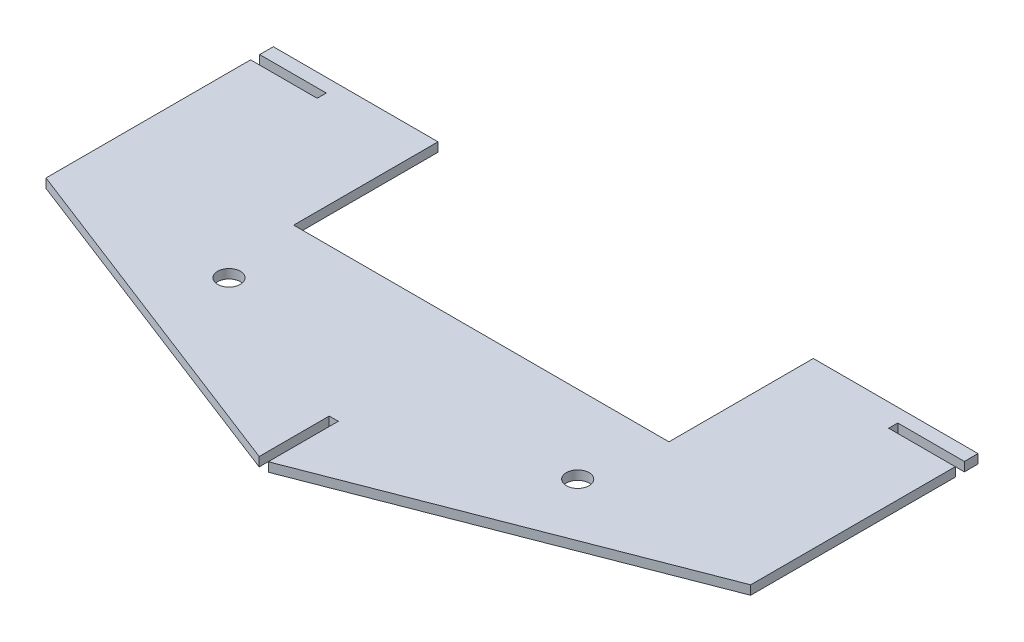
SolidWorks part; units mm, degrees
ref_plane "Front Plane" through (0, 0, 0) normal (0, 0, 1) x (1, 0, 0)
ref_plane "Top Plane" through (0, 0, 0) normal (0, 1, 0) x (1, 0, 0)
ref_plane "Right Plane" through (0, 0, 0) normal (1, 0, 0) x (0, 0, -1)
sketch "Sketch1" plane through (0, 0, 0) normal (0, 1, 0) x (1, 0, 0)
  line L0 (0, -100) -> (155, -160)
  line L1 (0, 0) -> (310, 0)
  line L2 (0, 0) -> (0, -100)
  line L3 (0, -100) -> (310, -100)
  line L4 (310, 0) -> (310, -100)
  line L5 (155, -160) -> (310, -100)
  line L6 (155, -160) -> (155, -100) construction
  line L7 (0, -6) -> (29.3, -6)
  line L8 (0, -6) -> (0, -10)
  line L9 (0, -10) -> (29.3, -10)
  line L10 (29.3, -6) -> (29.3, -10)
  line L15 (153, -160) -> (157, -160)
  line L16 (153, -160) -> (153, -128.4)
  line L17 (153, -128.4) -> (157, -128.4)
  line L18 (157, -160) -> (157, -128.4)
  line L19 (310, -6) -> (310, -10)
  line L20 (310, -10) -> (280.7, -10)
  line L21 (280.7, -6) -> (280.7, -10)
  line L22 (310, -6) -> (280.7, -6)
  point P19 (155, -160)
  dimension "D1" = 310
  dimension "D2" = 100
  dimension "D3" = 60
  dimension "D4" = 29.3
  dimension "D5" = 4
  dimension "D6" = 6
  dimension "D7" = 31.6
extrude "Boss-Extrude1" add sketch "Sketch1" along normal blind 4 contours L0 L6 L3 | L4 L1 L2 L3 | L6 L5 L3
ref_plane "Plane1" through (155, 0, 0) normal (-1, 0, 0) x (0, 0, 1)
sketch "Sketch2" plane through (0, 4, 0) normal (0, 1, 0) x (1, 0, 0)
  line L0 (0, 0) -> (310, 0) construction
  line L1 (72.45, 0) -> (237.55, 0)
  line L2 (72.45, 0) -> (72.45, -63.5)
  line L3 (72.45, -63.5) -> (237.55, -63.5)
  line L4 (237.55, 0) -> (237.55, -63.5)
  line L5 (155, 2.2) -> (155, -2.2) construction
  point P6 (155, 0)
  dimension "D1" = 165.1
  dimension "D2" = 63.5
extrude "Cut-Extrude1" cut sketch "Sketch2" against normal through all
sketch "Sketch4" plane through (0, 4, 0) normal (0, 1, 0) x (1, 0, 0)
  line L0 (155, 2.2) -> (155, -2.2) construction
  line L1 (0, -100) -> (78.3, -100)
  line L2 (0, -100) -> (0, -97.8)
  line L3 (0, -97.8) -> (78.3, -97.8)
  line L4 (78.3, -100) -> (78.3, -97.8)
  line L5 (231.7, -100) -> (231.7, -97.8)
  line L6 (310, -97.8) -> (231.7, -97.8)
  line L7 (310, -100) -> (310, -97.8)
  line L8 (310, -100) -> (231.7, -100)
  circle A1 centre (78.3, -97.8) radius 5
  circle A2 centre (231.7, -97.8) radius 5
  dimension "D1" = 10
  dimension "D2" = 78.3
  dimension "D3" = 2.2
extrude "Cut-Extrude2" cut sketch "Sketch4" against normal blind 10 contours L1 A1 L3 L4 | L3 A1 L1 L4 | A2 L6 L5 L8 | A2 L8 L5 L6
